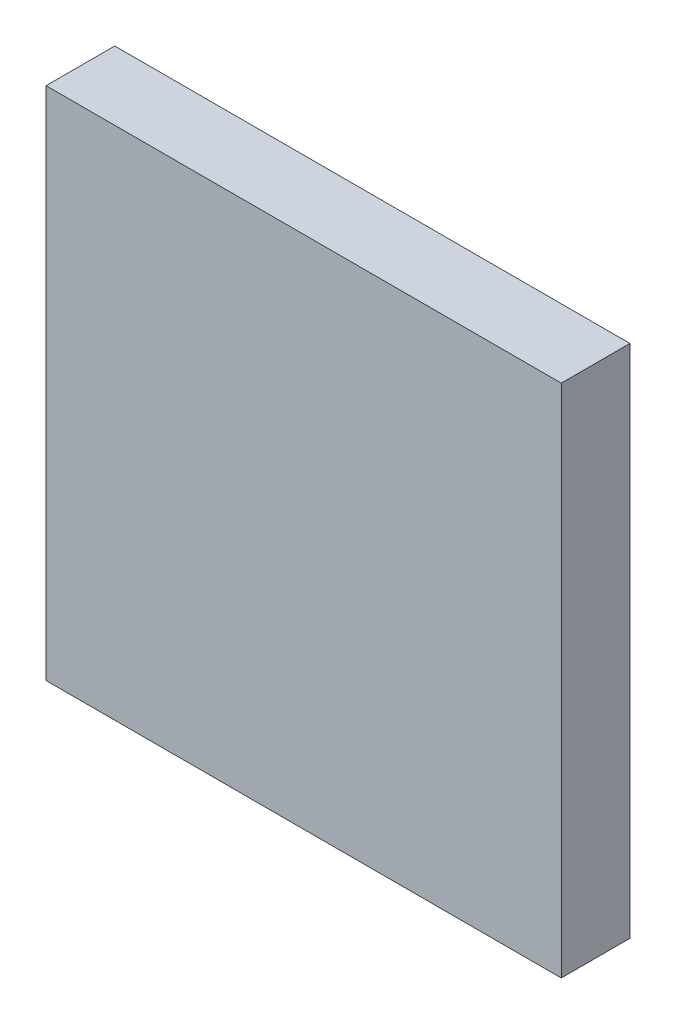
SolidWorks part; units mm, degrees
ref_plane "前视基准面" through (0, 0, 0) normal (0, 0, 1) x (1, 0, 0)
ref_plane "上视基准面" through (0, 0, 0) normal (0, 1, 0) x (1, 0, 0)
ref_plane "右视基准面" through (0, 0, 0) normal (1, 0, 0) x (0, 0, -1)
sketch "草图1" plane through (0, 0, 0) normal (0, 0, 1) x (1, 0, 0)
  line L1 (-60, -60) -> (60, -60)
  line L2 (-60, -60) -> (-60, 60)
  line L3 (-60, 60) -> (60, 60)
  line L4 (60, -60) -> (60, 60)
  line L5 (-60, -60) -> (60, 60) construction
  line L6 (-60, 60) -> (60, -60) construction
  point P0 (0, 0)
  dimension "D1" = 120
  dimension "D2" = 120
extrude "凸台-拉伸1" add sketch "草图1" along normal blind 16
